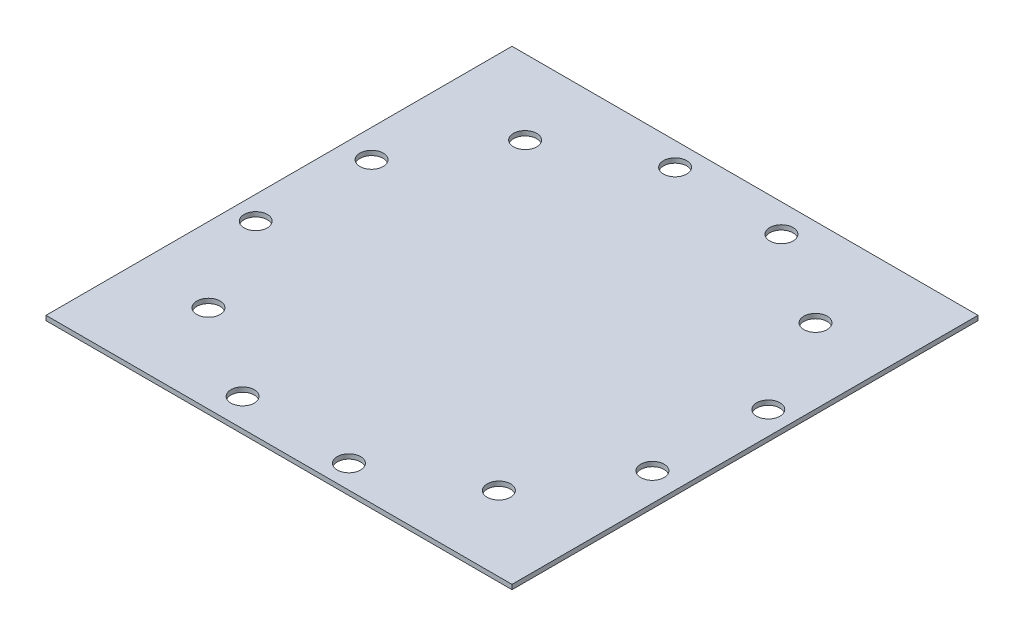
SolidWorks part; units mm, degrees
ref_plane "Front Plane" through (0, 0, 0) normal (0, 0, 1) x (1, 0, 0)
ref_plane "Top Plane" through (0, 0, 0) normal (0, 1, 0) x (1, 0, 0)
ref_plane "Right Plane" through (0, 0, 0) normal (1, 0, 0) x (0, 0, -1)
sketch "Sketch1" plane through (0, 0, 0) normal (0, 1, 0) x (1, 0, 0)
  line L0 (127, -127) -> (-127, 127) construction
  line L1 (-127, 127) -> (127, 127)
  line L2 (-127, 127) -> (-127, -127)
  line L3 (-127, -127) -> (127, -127)
  line L4 (127, 127) -> (127, -127)
  dimension "D1" = 254
extrude "Boss-Extrude1" add sketch "Sketch1" along normal blind 2.54
sketch "Sketch2" plane through (0, 2.54, 0) normal (0, 1, 0) x (1, 0, 0)
  line L0 (114.3, 0) -> (114.3, 25.4) construction
  circle A0 centre (0, 0) radius 114.3 construction
  circle A1 centre (114.3, 25.4) radius 6.35
  circle A2 centre (111.6867, -35.153) radius 6.35
  circle A3 centre (79.147, -86.2867) radius 6.35
  circle A4 centre (25.4, -114.3) radius 6.35
  circle A5 centre (-35.153, -111.6867) radius 6.35
  circle A6 centre (-86.2867, -79.147) radius 6.35
  circle A7 centre (-114.3, -25.4) radius 6.35
  circle A8 centre (-111.6867, 35.153) radius 6.35
  circle A9 centre (-79.147, 86.2867) radius 6.35
  circle A10 centre (-25.4, 114.3) radius 6.35
  circle A11 centre (35.153, 111.6867) radius 6.35
  circle A12 centre (86.2867, 79.147) radius 6.35
  point P31 (0, 0)
  dimension "D1" = 228.6
  dimension "D3" = 12.7
  dimension "D2" = 25.4
  dimension "D4" = 12
extrude "Cut-Extrude1" cut sketch "Sketch2" against normal through all
